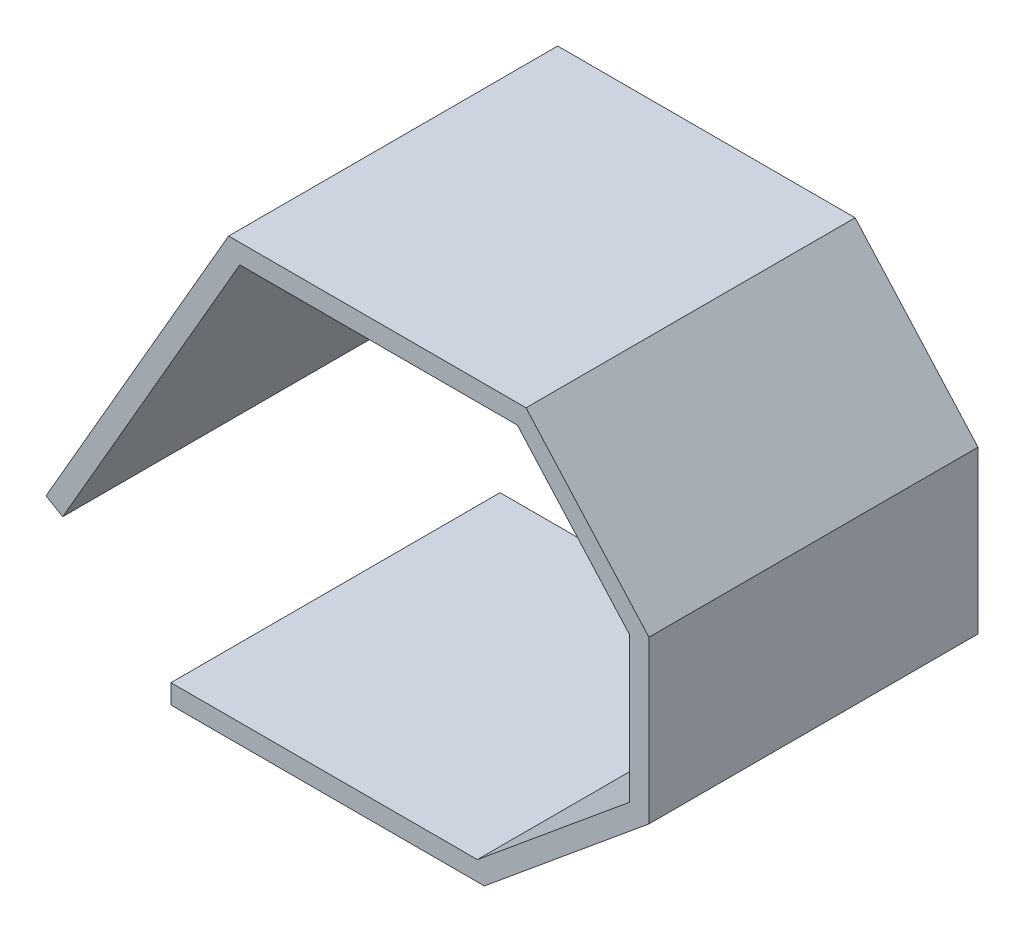
SolidWorks part; units mm, degrees
ref_plane "Front Plane" through (0, 0, 0) normal (0, 0, 1) x (1, 0, 0)
ref_plane "Top Plane" through (0, 0, 0) normal (0, 1, 0) x (1, 0, 0)
ref_plane "Right Plane" through (0, 0, 0) normal (1, 0, 0) x (0, 0, -1)
sketch "Sketch1" plane through (0, 0, 0) normal (0, 0, 1) x (1, 0, 0)
  line L0 (-117.0509, -44.076) -> (41.2407, -44.076)
  line L1 (41.2407, -44.076) -> (119.8557, 20.8781)
  line L2 (119.8557, 20.8781) -> (119.8557, 95.8846)
  line L3 (119.8557, 95.8846) -> (61.9181, 160.6267)
  line L4 (61.9181, 160.6267) -> (-81.486, 160.6267)
  line L5 (-81.486, 160.6267) -> (-172.9275, 2.2454)
  line L6 (-117.0509, -54.076) -> (44.8374, -54.076)
  line L7 (44.8374, -54.076) -> (129.8557, 16.1687)
  line L8 (129.8557, 16.1687) -> (129.8557, 99.7057)
  line L9 (129.8557, 99.7057) -> (66.3887, 170.6267)
  line L10 (66.3887, 170.6267) -> (-87.2595, 170.6267)
  line L11 (-87.2595, 170.6267) -> (-181.5877, 7.2454)
  line L12 (-117.0509, -44.076) -> (-117.0509, -54.076)
  line L13 (-172.9275, 2.2454) -> (-181.5877, 7.2454)
  line L14 (-136.786, -101.4551) -> (-136.786, 64.8443) construction
  line L15 (-136.786, 64.8443) -> (-28.9497, 2.585) construction
  line L16 (-136.786, 64.8443) -> (29.1141, 160.6267) construction
  point P16 (-251.7396, -121.8612)
  point P17 (8.0172, 136.2922)
  point P19 (29.9308, 160.6267)
  dimension "D1" = 10
  dimension "D2" = 140.435
  dimension "D3" = 72.283
  dimension "D4" = 188.6565
  dimension "D5" = 30
  dimension "ang1" = 30
extrude "Boss-Extrude1" add sketch "Sketch1" along normal blind 170
